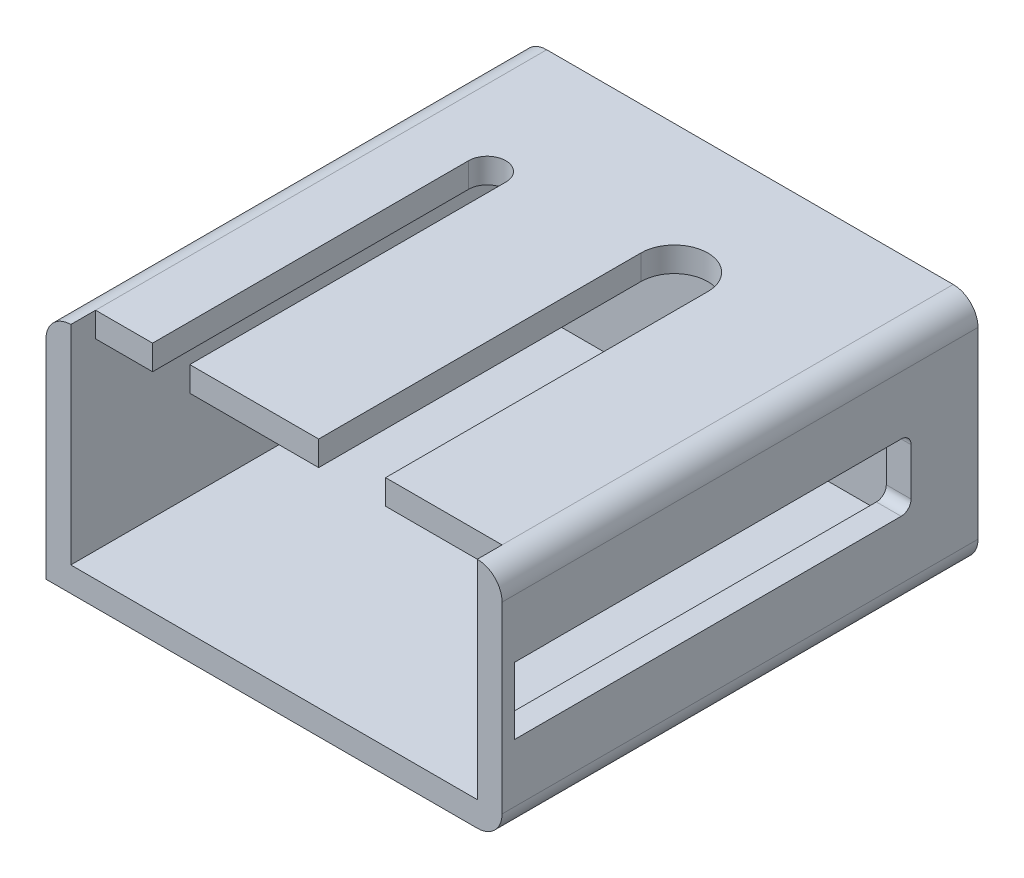
SolidWorks part; units mm, degrees
ref_plane "前视基准面" through (0, 0, 0) normal (0, 0, 1) x (1, 0, 0)
ref_plane "上视基准面" through (0, 0, 0) normal (0, 1, 0) x (1, 0, 0)
ref_plane "右视基准面" through (0, 0, 0) normal (1, 0, 0) x (0, 0, -1)
sketch "草图1" plane through (0, 0, 0) normal (0, 0, 1) x (1, 0, 0)
  line L4 (-82, 37) -> (-82, -37)
  line L5 (-82, -37) -> (82, -37)
  line L6 (82, -37) -> (82, 37)
  line L7 (82, 37) -> (-82, 37)
  line L12 (-92, 47) -> (-92, -47)
  line L13 (-92, -47) -> (92, -47)
  line L14 (92, -47) -> (92, 47)
  line L15 (92, 47) -> (-92, 47)
  dimension "D1" = 10
extrude "凸台-拉伸1" add sketch "草图1" against normal offset from surface (192 mm away) 12
sketch "草图2" plane through (0, 0, -192) normal (0, 0, -1) x (-1, 0, 0)
  line L4 (92, 47) -> (-92, 47)
  line L5 (-92, 47) -> (-92, -47)
  line L6 (-92, -47) -> (92, -47)
  line L7 (92, -47) -> (92, 47)
  line L8 (92, 47) -> (-92, 47)
  line L9 (-92, 47) -> (-92, -47)
  line L10 (-92, -47) -> (92, -47)
  line L11 (92, -47) -> (92, 47)
  dimension "D1" = 0
extrude "凸台-拉伸2" add sketch "草图2" against normal blind 10
sketch "草图3" plane through (0, 47, 0) normal (0, 1, 0) x (1, 0, 0)
  line L1 (35, 140) -> (35, 40)
  line L3 (8, 40) -> (8, 140)
  line L6 (-59, 42.5) -> (-59, 137.5)
  line L7 (-44, 137.5) -> (-44, 42.5)
  arc A1 (35, 140) -> (8, 140) centre (21.5, 140) ccw
  arc A5 (-59, 42.5) -> (-44, 42.5) centre (-51.5, 42.5) ccw
  arc A6 (-44, 137.5) -> (-59, 137.5) centre (-51.5, 137.5) ccw
  arc A7 (8, 40) -> (35, 40) centre (21.5, 40) ccw
extrude "切除-拉伸1" cut sketch "草图3" against normal up to next
sketch "草图4" plane through (92, 0, 0) normal (1, 0, 0) x (0, 0, -1)
  line L4 (15, 9.5) -> (15, -9.5)
  line L5 (161, 13.5) -> (19, 13.5)
  line L6 (165, -9.5) -> (165, 9.5)
  line L7 (19, -13.5) -> (161, -13.5)
  arc A4 (15, -9.5) -> (19, -13.5) centre (19, -9.5) ccw
  arc A5 (19, 13.5) -> (15, 9.5) centre (19, 9.5) ccw
  arc A6 (165, 9.5) -> (161, 13.5) centre (161, 9.5) ccw
  arc A7 (161, -13.5) -> (165, -9.5) centre (161, -9.5) ccw
extrude "切除-拉伸2" cut sketch "草图4" against normal up to next
sketch "草图5" plane through (0, 47, 0) normal (0, 1, 0) x (1, 0, 0)
  line L0 (8, 40) -> (8, -14.8305)
  line L1 (8, -14.8305) -> (37.5701, -14.8305)
  line L2 (35, 40) -> (35, -14.8305)
  line L3 (-44, 42.5) -> (-44, -20.1461)
  line L4 (-44, 42.5) -> (-44, 137.5) construction
  line L5 (-59, 42.5) -> (-59, -20.1461)
  line L6 (-59, -20.1461) -> (-44, -20.1461)
  line L7 (-59, 42.5) -> (-44, 42.5)
  line L8 (8, 40) -> (35, 40)
  arc A0 (8, 40) -> (35, 40) centre (21.5, 40) ccw construction
  arc A1 (-59, 42.5) -> (-44, 42.5) centre (-51.5, 42.5) ccw construction
  arc M3 (35, 40) -> (8, 40) centre (21.5, 40) cw
  arc M5 (-44, 42.5) -> (-59, 42.5) centre (-51.5, 42.5) cw
  line M10 (-92, 0) -> (92, 0)
extrude "切除-拉伸3" cut sketch "草图5" against normal blind 10 contours L2 L0 M3 M10 | L5 L3 M5 M10
sketch "草图7" plane through (92, 0, 0) normal (1, 0, 0) x (0, 0, -1)
  line L0 (18.4351, 13.4599) -> (-12.8309, 13.4599)
  line L1 (19, -13.5) -> (-16.8829, -13.5)
  line L2 (-16.8829, -13.5) -> (-12.8309, 13.4599)
  line L3 (18.4351, 13.4599) -> (19, -13.5)
  arc A0 (19, 13.5) -> (15, 9.5) centre (19, 9.5) ccw construction
  arc A1 (15, -9.5) -> (19, -13.5) centre (19, -9.5) ccw construction
extrude "切除-拉伸4" cut sketch "草图7" against normal blind 10
sketch "草图8" plane through (92, 0, 0) normal (1, 0, 0) x (0, 0, -1)
  line L0 (0, 13.4599) -> (0, 47) construction
  line L1 (0, 13.4599) -> (5, 13.4599)
  line L2 (0, 13.4599) -> (0, -13.5)
  line L3 (0, -13.5) -> (5, -13.5)
  line L4 (5, 13.4599) -> (5, -13.5)
  line L5 (0, -13.5) -> (161, -13.5) construction
  dimension "D1" = 5
extrude "凸台-拉伸4" add sketch "草图8" against normal up to surface (10 mm away) up to face at (82, 2.2442, -87.9243)
sketch "草图9" plane through (0, 47, 0) normal (0, 1, 0) x (1, 0, 0)
  line L0 (-59, 0) -> (-82, 0) construction
  line L1 (-59, 0) -> (-82, 0)
  line L2 (82, 0) -> (35, 0) construction
  line L3 (82, 0) -> (35, 0)
  line L5 (-82, 0) -> (82, 0)
  line L6 (-82, 0) -> (-82, 10)
  line L7 (-82, 10) -> (82, 10)
  line L8 (82, 0) -> (82, 10)
  line M5 (35, 140) -> (35, 0)
  line M6 (35, 0) -> (92, 0)
  line M10 (-92, 0) -> (-59, 0)
  line M11 (-59, 0) -> (-59, 137.5)
  line M13 (-44, 137.5) -> (-44, 0)
  line M14 (-44, 0) -> (8, 0)
  line M15 (8, 0) -> (8, 140)
  dimension "D1" = 10
  dimension "D2" = 164
extrude "切除-拉伸5" cut sketch "草图9" against normal blind 10 contours L7 M13 M14 M15 | L7 L6 M10 M11 | L8 L7 M6 M5
fillet "圆角1" radius 10 3 edges at (-92, 47, -96) (92, 47, -96) (92, -47, -96)
